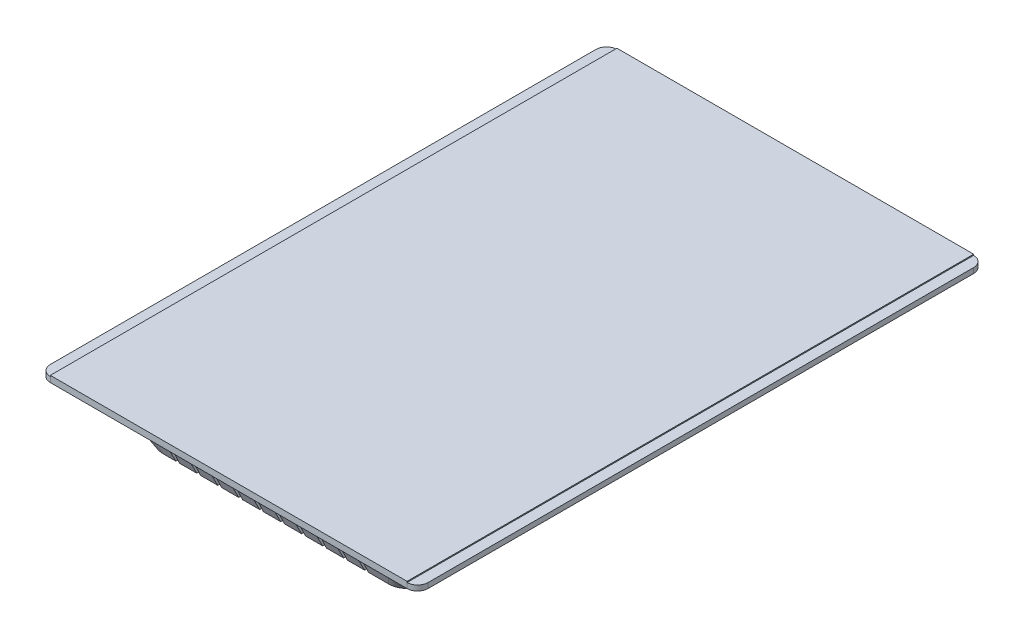
SolidWorks part; units mm, degrees
other "Camera1"
ref_plane "Front Plane" through (0, 0, 0) normal (0, 0, 1) x (1, 0, 0)
ref_plane "Top Plane" through (0, 0, 0) normal (0, 1, 0) x (1, 0, 0)
ref_plane "Right Plane" through (0, 0, 0) normal (1, 0, 0) x (0, 0, -1)
sketch "Sketch1" plane through (0, 0, 0) normal (0, 1, 0) x (1, 0, 0)
  line L1 (150, 250) -> (-150, 250)
  line L2 (150, 250) -> (150, -250)
  line L3 (150, -250) -> (-150, -250)
  line L4 (-150, 250) -> (-150, -250)
  line L5 (150, 250) -> (-150, -250) construction
  line L6 (150, -250) -> (-150, 250) construction
  point P0 (0, 0)
  dimension "D1" = 500
  dimension "D2" = 300
ref_plane "Plane1" through (0, -50, 0) normal (0, 1, 0) x (1, 0, 0)
sketch "Sketch2" plane through (0, -50, 0) normal (0, 1, 0) x (1, 0, 0)
  line L1 (-125, -225) -> (125, -225)
  line L2 (-125, -225) -> (-125, 225)
  line L3 (-125, 225) -> (125, 225)
  line L4 (125, -225) -> (125, 225)
  line L5 (-125, -225) -> (125, 225) construction
  line L6 (-125, 225) -> (125, -225) construction
  point P0 (0, 0)
  dimension "D1" = 450
  dimension "D2" = 250
loft "Loft1" add profiles "Sketch1", "Sketch2"
fillet "Fillet1" radius 20 4 edges
sketch "Sketch3" plane through (0, 0, 0) normal (0, 1, 0) x (1, 0, 0)
  line L1 (-180, -270) -> (180, -270)
  line L2 (-180, -270) -> (-180, 270)
  line L3 (-180, 270) -> (180, 270)
  line L4 (180, -270) -> (180, 270)
  line L5 (-180, -270) -> (180, 270) construction
  line L6 (-180, 270) -> (180, -270) construction
  point P0 (0, 0)
  dimension "D1" = 540
  dimension "D2" = 360
extrude "Boss-Extrude1" add sketch "Sketch3" along normal blind 5 contours L1 L4 L3 L2
fillet "Fillet2" radius 10 4 edges at (-180, 2.5, -270) (180, 2.5, -270) (-180, 2.5, 270) (180, 2.5, 270)
sketch "Sketch4" plane through (0, 5, 0) normal (0, 1, 0) x (1, 0, 0)
  line L1 (-170, -270) -> (170, -270)
  line L2 (-170, -270) -> (-170, 270)
  line L3 (-170, 270) -> (170, 270)
  line L4 (170, -270) -> (170, 270)
  line L5 (-170, -270) -> (170, 270) construction
  line L6 (-170, 270) -> (170, -270) construction
  line L7 (-170, 270) -> (170, 270) construction
  arc A1 (180, 260) -> (170, 270) centre (170, 260) ccw construction
  point P0 (0, 0)
  dimension "D1" = 540
  dimension "D2" = 340
extrude "Boss-Extrude2" add sketch "Sketch4" along normal blind 1
ref_plane "Plane2" through (-100, 0, 0) normal (1, 0, 0) x (0, 0, -1)
sketch "Sketch5" plane through (-100, 0, 0) normal (1, 0, 0) x (0, 0, -1)
  line L0 (167.1115, -50) -> (167.1115, -85.0109) construction
  line L1 (-207.1115, -50) -> (207.1115, -50) construction
  line L2 (167.1115, -50) -> (167.1115, -70)
  line L3 (156.6176, -50) -> (167.1115, -50)
  line L4 (156.6176, -50) -> (159.3076, -63.7365)
  arc A0 (167.1115, -70) -> (159.3076, -63.7365) centre (167.1115, -62.0068) cw
  dimension "D1" = 40
  dimension "D2" = 20
revolve "Revolve2" add sketch "Sketch5" angle 360 about L0
mirror "Mirror1" about plane through (0, 0, 0) normal (0, 0, 1) of "Revolve2"
mirror "Mirror2" about plane through (0, 0, 0) normal (1, 0, 0) of "Mirror1", "Revolve2"
sketch "Sketch7" plane through (0, 0, 0) normal (1, 0, 0) x (0, 0, -1)
  line L0 (-186.2612, -50) -> (-186.2612, -60.9992)
  line L1 (-207.1115, -50) -> (207.1115, -50) construction
  line L2 (-186.2612, -60.9992) -> (-126.2364, -60.9992)
  line L3 (-126.2364, -60.9992) -> (-126.2364, -50)
  line L4 (-126.2364, -50) -> (-186.2612, -50)
  line L7 (-185.2488, -50.9996) -> (-127.2488, -50.9996)
  line L8 (-185.2488, -50.9996) -> (-185.2488, -59.9996)
  line L9 (-185.2488, -59.9996) -> (-127.2488, -59.9996)
  line L10 (-127.2488, -50.9996) -> (-127.2488, -59.9996)
  line L11 (-185.2488, -50.9996) -> (-127.2488, -59.9996) construction
  line L12 (-185.2488, -59.9996) -> (-127.2488, -50.9996) construction
  point P4 (-156.2488, -55.4996)
revolve "Revolve4" add sketch "Sketch7" angle 360 about L3
sketch "Sketch8" plane through (0, -60.9992, 0) normal (0, -1, 0) x (1, 0, 0)
  line L0 (-4.026, 182.8975) -> (-1.9496, 173.1089)
  line L1 (-1.9496, 173.1089) -> (0, 173.1089)
  line L2 (0, 173.1089) -> (-2.0764, 182.8975)
  line L3 (-2.0764, 182.8975) -> (-4.026, 182.8975)
  line L4 (-19.484, 179.4827) -> (-21.3381, 178.8802)
  line L5 (-21.3381, 178.8802) -> (-16.3386, 170.2124)
  line L6 (-16.3386, 170.2124) -> (-14.4844, 170.8148)
  line L7 (-14.4844, 170.8148) -> (-19.484, 179.4827)
  line L8 (-34.9843, 170.8557) -> (-36.5616, 169.7098)
  line L9 (-36.5616, 169.7098) -> (-29.1282, 163.0111)
  line L10 (-29.1282, 163.0111) -> (-27.551, 164.1571)
  line L11 (-27.551, 164.1571) -> (-34.9843, 170.8557)
  line L12 (-47.0602, 157.8611) -> (-48.2062, 156.2839)
  line L13 (-48.2062, 156.2839) -> (-39.0666, 152.2101)
  line L14 (-39.0666, 152.2101) -> (-37.9206, 153.7874)
  line L15 (-37.9206, 153.7874) -> (-47.0602, 157.8611)
  line L16 (-54.5295, 141.7709) -> (-55.132, 139.9167)
  line L17 (-55.132, 139.9167) -> (-45.1809, 138.8666)
  line L18 (-45.1809, 138.8666) -> (-44.5784, 140.7208)
  line L19 (-44.5784, 140.7208) -> (-54.5295, 141.7709)
  line L20 (-56.6611, 124.1601) -> (-56.6611, 122.2105)
  line L21 (-56.6611, 122.2105) -> (-46.8725, 124.2868)
  line L22 (-46.8725, 124.2868) -> (-46.8725, 126.2364)
  line L23 (-46.8725, 126.2364) -> (-56.6611, 124.1601)
  line L24 (-53.2462, 106.7525) -> (-52.6438, 104.8983)
  line L25 (-52.6438, 104.8983) -> (-43.9759, 109.8978)
  line L26 (-43.9759, 109.8978) -> (-44.5784, 111.752)
  line L27 (-44.5784, 111.752) -> (-53.2462, 106.7525)
  line L28 (-44.6193, 91.2521) -> (-43.4734, 89.6748)
  line L29 (-43.4734, 89.6748) -> (-36.7747, 97.1082)
  line L30 (-36.7747, 97.1082) -> (-37.9206, 98.6855)
  line L31 (-37.9206, 98.6855) -> (-44.6193, 91.2521)
  line L32 (-31.6247, 79.1762) -> (-30.0475, 78.0303)
  line L33 (-30.0475, 78.0303) -> (-25.9737, 87.1698)
  line L34 (-25.9737, 87.1698) -> (-27.551, 88.3158)
  line L35 (-27.551, 88.3158) -> (-31.6247, 79.1762)
  line L36 (-15.5345, 71.7069) -> (-13.6803, 71.1045)
  line L37 (-13.6803, 71.1045) -> (-12.6302, 81.0556)
  line L38 (-12.6302, 81.0556) -> (-14.4844, 81.658)
  line L39 (-14.4844, 81.658) -> (-15.5345, 71.7069)
  line L40 (2.0764, 69.5754) -> (4.026, 69.5754)
  line L41 (4.026, 69.5754) -> (1.9496, 79.3639)
  line L42 (1.9496, 79.3639) -> (0, 79.3639)
  line L43 (0, 79.3639) -> (2.0764, 69.5754)
  line L44 (19.484, 72.9902) -> (21.3381, 73.5926)
  line L45 (21.3381, 73.5926) -> (16.3386, 82.2605)
  line L46 (16.3386, 82.2605) -> (14.4844, 81.658)
  line L47 (14.4844, 81.658) -> (19.484, 72.9902)
  line L48 (34.9843, 81.6171) -> (36.5616, 82.7631)
  line L49 (36.5616, 82.7631) -> (29.1282, 89.4617)
  line L50 (29.1282, 89.4617) -> (27.551, 88.3158)
  line L51 (27.551, 88.3158) -> (34.9843, 81.6171)
  line L52 (47.0602, 94.6117) -> (48.2062, 96.189)
  line L53 (48.2062, 96.189) -> (39.0666, 100.2627)
  line L54 (39.0666, 100.2627) -> (37.9206, 98.6855)
  line L55 (37.9206, 98.6855) -> (47.0602, 94.6117)
  line L56 (54.5295, 110.7019) -> (55.132, 112.5561)
  line L57 (55.132, 112.5561) -> (45.1809, 113.6062)
  line L58 (45.1809, 113.6062) -> (44.5784, 111.752)
  line L59 (44.5784, 111.752) -> (54.5295, 110.7019)
  line L60 (56.6611, 128.3128) -> (56.6611, 130.2624)
  line L61 (56.6611, 130.2624) -> (46.8725, 128.186)
  line L62 (46.8725, 128.186) -> (46.8725, 126.2364)
  line L63 (46.8725, 126.2364) -> (56.6611, 128.3128)
  line L64 (53.2462, 145.7204) -> (52.6438, 147.5746)
  line L65 (52.6438, 147.5746) -> (43.9759, 142.575)
  line L66 (43.9759, 142.575) -> (44.5784, 140.7208)
  line L67 (44.5784, 140.7208) -> (53.2462, 145.7204)
  line L68 (44.6193, 161.2208) -> (43.4734, 162.798)
  line L69 (43.4734, 162.798) -> (36.7747, 155.3646)
  line L70 (36.7747, 155.3646) -> (37.9206, 153.7874)
  line L71 (37.9206, 153.7874) -> (44.6193, 161.2208)
  line L72 (31.6247, 173.2966) -> (30.0475, 174.4426)
  line L73 (30.0475, 174.4426) -> (25.9737, 165.303)
  line L74 (25.9737, 165.303) -> (27.551, 164.1571)
  line L75 (27.551, 164.1571) -> (31.6247, 173.2966)
  line L76 (15.5345, 180.7659) -> (13.6803, 181.3684)
  line L77 (13.6803, 181.3684) -> (12.6302, 171.4173)
  line L78 (12.6302, 171.4173) -> (14.4844, 170.8148)
  line L79 (14.4844, 170.8148) -> (15.5345, 180.7659)
  line L80 (-1.9496, 165.303) -> (0.1268, 159.1701)
  line L81 (0.1268, 159.1701) -> (2.0764, 159.1701)
  line L82 (2.0764, 159.1701) -> (0, 165.303)
  line L83 (0, 165.303) -> (-1.9496, 165.303)
  line L84 (0.1268, 151.1107) -> (2.0764, 144.5893)
  line L85 (2.0764, 144.5893) -> (4.026, 144.5893)
  line L86 (4.026, 144.5893) -> (2.0764, 151.1107)
  line L87 (2.0764, 151.1107) -> (0.1268, 151.1107)
  line L88 (3.7204, 138.8666) -> (5.3218, 133.2921)
  line L89 (5.3218, 133.2921) -> (6.8652, 133.2921)
  line L90 (6.8652, 133.2921) -> (5.3218, 138.8666)
  line L91 (5.3218, 138.8666) -> (3.7204, 138.8666)
  line L92 (14.1088, 162.7185) -> (13.5111, 156.2713)
  line L93 (15.8898, 161.9255) -> (14.1088, 162.7185)
  line L94 (13.5111, 156.2713) -> (15.2922, 155.4783)
  line L95 (15.2922, 155.4783) -> (15.8898, 161.9255)
  line L96 (27.7276, 153.8259) -> (24.5593, 148.1792)
  line L97 (29.0321, 152.3771) -> (27.7276, 153.8259)
  line L98 (24.5593, 148.1792) -> (25.8639, 146.7303)
  line L99 (25.8639, 146.7303) -> (29.0321, 152.3771)
  line L100 (36.5521, 140.1628) -> (31.361, 136.2929)
  line L101 (37.1545, 138.3087) -> (36.5521, 140.1628)
  line L102 (31.361, 136.2929) -> (31.9634, 134.4388)
  line L103 (31.9634, 134.4388) -> (37.1545, 138.3087)
  line L104 (39.0564, 124.0918) -> (32.74, 122.6679)
  line L105 (38.8526, 122.1529) -> (39.0564, 124.0918)
  line L106 (32.74, 122.6679) -> (32.5362, 120.7289)
  line L107 (32.5362, 120.7289) -> (38.8526, 122.1529)
  line L108 (34.8075, 108.3915) -> (28.458, 109.6598)
  line L109 (33.8327, 106.7031) -> (34.8075, 108.3915)
  line L110 (28.458, 109.6598) -> (27.4832, 107.9714)
  line L111 (27.4832, 107.9714) -> (33.8327, 106.7031)
  line L112 (24.54, 95.7768) -> (19.2554, 99.518)
  line L113 (22.9628, 94.6309) -> (24.54, 95.7768)
  line L114 (19.2554, 99.518) -> (17.6781, 98.3721)
  line L115 (17.6781, 98.3721) -> (22.9628, 94.6309)
  line L116 (10.0294, 88.4289) -> (6.7233, 93.9961)
  line L117 (8.1224, 88.0235) -> (10.0294, 88.4289)
  line L118 (6.7233, 93.9961) -> (4.8163, 93.5907)
  line L119 (4.8163, 93.5907) -> (8.1224, 88.0235)
  line L120 (-6.2154, 87.6182) -> (-6.9713, 94.0488)
  line L121 (-8.1224, 88.0235) -> (-6.2154, 87.6182)
  line L122 (-6.9713, 94.0488) -> (-8.8783, 94.4541)
  line L123 (-8.8783, 94.4541) -> (-8.1224, 88.0235)
  line L124 (-21.3855, 93.4849) -> (-19.4605, 99.667)
  line L125 (-22.9628, 94.6309) -> (-21.3855, 93.4849)
  line L126 (-19.4605, 99.667) -> (-21.0377, 100.813)
  line L127 (-21.0377, 100.813) -> (-22.9628, 94.6309)
  line L128 (-32.8579, 105.0147) -> (-28.5848, 109.8794)
  line L129 (-33.8327, 106.7031) -> (-32.8579, 105.0147)
  line L130 (-28.5848, 109.8794) -> (-29.5596, 111.5678)
  line L131 (-29.5596, 111.5678) -> (-33.8327, 106.7031)
  line L132 (-38.6488, 120.2139) -> (-32.7665, 122.92)
  line L133 (-38.8526, 122.1529) -> (-38.6488, 120.2139)
  line L134 (-32.7665, 122.92) -> (-32.9703, 124.8589)
  line L135 (-32.9703, 124.8589) -> (-38.8526, 122.1529)
  line L136 (-37.757, 136.4545) -> (-31.2826, 136.534)
  line L137 (-37.1545, 138.3087) -> (-37.757, 136.4545)
  line L138 (-31.2826, 136.534) -> (-30.6802, 138.3882)
  line L139 (-30.6802, 138.3882) -> (-37.1545, 138.3087)
  line L140 (-30.3367, 150.9282) -> (-24.3897, 148.3676)
  line L141 (-29.0321, 152.3771) -> (-30.3367, 150.9282)
  line L142 (-24.3897, 148.3676) -> (-23.0851, 149.8164)
  line L143 (-23.0851, 149.8164) -> (-29.0321, 152.3771)
  line L144 (-17.6709, 161.1326) -> (-13.2795, 156.3744)
  line L145 (-15.8898, 161.9255) -> (-17.6709, 161.1326)
  line L146 (-13.2795, 156.3744) -> (-11.4985, 157.1674)
  line L147 (-11.4985, 157.1674) -> (-15.8898, 161.9255)
  line L148 (14.0446, 138.7178) -> (16.3005, 145.1396)
  line L149 (12.4674, 139.8638) -> (14.0446, 138.7178)
  line L150 (14.7233, 146.2856) -> (12.4674, 139.8638)
  line L151 (16.3005, 145.1396) -> (14.7233, 146.2856)
  line L152 (18.6988, 128.0789) -> (24.2984, 131.9482)
  line L153 (18.0963, 129.9331) -> (18.6988, 128.0789)
  line L154 (23.696, 133.8024) -> (18.0963, 129.9331)
  line L155 (24.2984, 131.9482) -> (23.696, 133.8024)
  line L156 (16.2106, 116.7361) -> (23.0152, 116.5751)
  line L157 (16.813, 118.5903) -> (16.2106, 116.7361)
  line L158 (23.6176, 118.4293) -> (16.813, 118.5903)
  line L159 (23.0152, 116.5751) -> (23.6176, 118.4293)
  line L160 (7.5305, 109.0222) -> (12.9409, 104.8923)
  line L161 (9.1078, 110.1681) -> (7.5305, 109.0222)
  line L162 (14.5182, 106.0382) -> (9.1078, 110.1681)
  line L163 (12.9409, 104.8923) -> (14.5182, 106.0382)
  line L164 (-4.026, 107.8835) -> (-2.0764, 101.3622)
  line L165 (-2.0764, 107.8835) -> (-4.026, 107.8835)
  line L166 (-0.1268, 101.3622) -> (-2.0764, 107.8835)
  line L167 (-2.0764, 101.3622) -> (-0.1268, 101.3622)
  line L168 (-14.0446, 113.755) -> (-16.3005, 107.3332)
  line L169 (-12.4674, 112.6091) -> (-14.0446, 113.755)
  line L170 (-14.7233, 106.1873) -> (-12.4674, 112.6091)
  line L171 (-16.3005, 107.3332) -> (-14.7233, 106.1873)
  line L172 (-18.6988, 124.394) -> (-24.2984, 120.5246)
  line L173 (-18.0963, 122.5398) -> (-18.6988, 124.394)
  line L174 (-23.696, 118.6704) -> (-18.0963, 122.5398)
  line L175 (-24.2984, 120.5246) -> (-23.696, 118.6704)
  line L176 (-16.2106, 135.7367) -> (-23.0152, 135.8977)
  line L177 (-16.813, 133.8825) -> (-16.2106, 135.7367)
  line L178 (-23.6176, 134.0435) -> (-16.813, 133.8825)
  line L179 (-23.0152, 135.8977) -> (-23.6176, 134.0435)
  line L180 (-7.5305, 143.4506) -> (-12.9409, 147.5806)
  line L181 (-9.1078, 142.3047) -> (-7.5305, 143.4506)
  line L182 (-14.5182, 146.4346) -> (-9.1078, 142.3047)
  line L183 (-12.9409, 147.5806) -> (-14.5182, 146.4346)
  line L184 (8.8318, 121.8875) -> (13.6566, 125.078)
  line L185 (8.3548, 123.3554) -> (8.8318, 121.8875)
  line L186 (13.1617, 126.6011) -> (8.3548, 123.3554)
  line L187 (13.6566, 125.078) -> (13.1617, 126.6011)
  line L188 (-1.4069, 116.493) -> (3.1184, 112.8903)
  line L189 (-0.1582, 117.4002) -> (-1.4069, 116.493)
  line L190 (4.414, 113.8316) -> (-0.1582, 117.4002)
  line L191 (3.1184, 112.8903) -> (4.414, 113.8316)
  line L192 (-9.7013, 124.5636) -> (-11.7293, 119.1464)
  line L193 (-8.4526, 123.6564) -> (-9.7013, 124.5636)
  line L194 (-10.4337, 118.2051) -> (-8.4526, 123.6564)
  line L195 (-11.7293, 119.1464) -> (-10.4337, 118.2051)
  line L196 (-4.5888, 134.9459) -> (-10.3675, 135.2007)
  line L197 (-5.0658, 133.4781) -> (-4.5888, 134.9459)
  line L198 (-10.8624, 133.6776) -> (-5.0658, 133.4781)
  line L199 (-10.3675, 135.2007) -> (-10.8624, 133.6776)
  point P82 (0, 126.2364)
  point P151 (0, 126.2364)
  point P188 (0, 126.2364)
  point P205 (0, 126.2364)
  dimension "D1" = 20
  dimension "D2" = 15
  dimension "D3" = 10
  dimension "D4" = 5
extrude "Cut-Extrude1" cut sketch "Sketch8" against normal blind 8
sketch "Sketch9" plane through (0, 0, 0) normal (1, 0, 0) x (0, 0, -1)
  line L1 (-131.1706, -51.1399) -> (-128.3169, -51.1399)
  line L2 (-131.1706, -51.1399) -> (-131.1706, -59.7009)
  line L3 (-131.1706, -59.7009) -> (-128.3169, -59.7009)
  line L4 (-128.3169, -51.1399) -> (-128.3169, -59.7009)
extrude "Cut-Extrude2" cut sketch "Sketch9" against normal blind 68 and the other way blind 78
pattern_circular "CirPattern1" count 12 every 15 about axis through (0, 0, 126.2364) along (0, 1, 0) of "Cut-Extrude2"
ref_plane "Plane3" through (0, 0, -310) normal (0, 0, 1) x (1, 0, 0)
sketch "Sketch10" plane through (0, 0, -310) normal (0, 0, 1) x (1, 0, 0)
  line L0 (10.7135, -4.044) -> (8.1167, -50.898)
  line L1 (8.1167, -50.898) -> (4.6317, -50.898)
  line L2 (4.6317, -50.898) -> (2.5886, -4.044)
  line L3 (10.7135, -4.044) -> (2.5886, -4.044)
extrude "Cut-Extrude3" cut sketch "Sketch10" along normal blind 88
pattern_linear "LPattern1" count 6 spacing 20 along (-1, 0, 0) count 5 spacing 20 along (1, 0, 0) of "Cut-Extrude3"
mirror "Mirror3" about plane through (0, 0, 0) normal (0, 0, 1) of "LPattern1", "Cut-Extrude3"
sketch "Sketch12" plane through (0, 6, 0) normal (0, 1, 0) x (1, 0, 0)
  line L0 (-43.7575, 429.3656) -> (430.2425, 429.3656) construction
